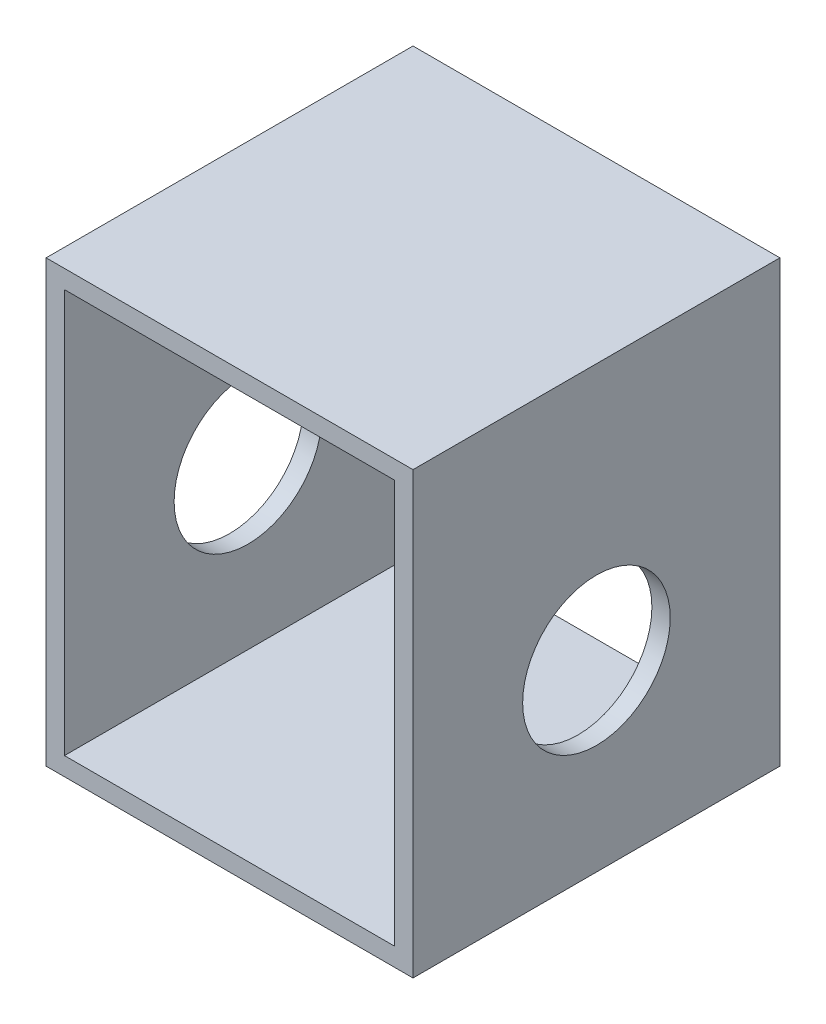
SolidWorks part; units mm, degrees
ref_plane "Front Plane" through (0, 0, 0) normal (0, 0, 1) x (1, 0, 0)
ref_plane "Top Plane" through (0, 0, 0) normal (0, 1, 0) x (1, 0, 0)
ref_plane "Right Plane" through (0, 0, 0) normal (1, 0, 0) x (0, 0, -1)
sketch "Sketch1" plane through (0, 0, 0) normal (0, 0, 1) x (1, 0, 0)
  line L1 (0, 0) -> (63.5, 0)
  line L2 (0, 0) -> (0, 76.2)
  line L3 (0, 76.2) -> (63.5, 76.2)
  line L4 (63.5, 0) -> (63.5, 76.2)
  line L5 (3.175, 73.025) -> (60.325, 73.025)
  line L6 (3.175, 73.025) -> (3.175, 3.175)
  line L7 (3.175, 3.175) -> (60.325, 3.175)
  line L8 (60.325, 73.025) -> (60.325, 3.175)
  dimension "D1" = 63.5
  dimension "D2" = 76.2
  dimension "D3" = 3.175
  dimension "D4" = 3.175
  dimension "D5" = 3.175
  dimension "D6" = 3.175
extrude "Boss-Extrude1" add sketch "Sketch1" along normal blind 63.5
sketch "Sketch2" plane through (0, 0, 0) normal (-1, 0, 0) x (0, 0, 1)
  line L0 (63.5, 76.2) -> (0, 76.2) construction
  circle A0 centre (31.75, 31.75) radius 12.7722
  dimension "D1" = 44.45
extrude "Cut-Extrude1" cut sketch "Sketch2" against normal through all
